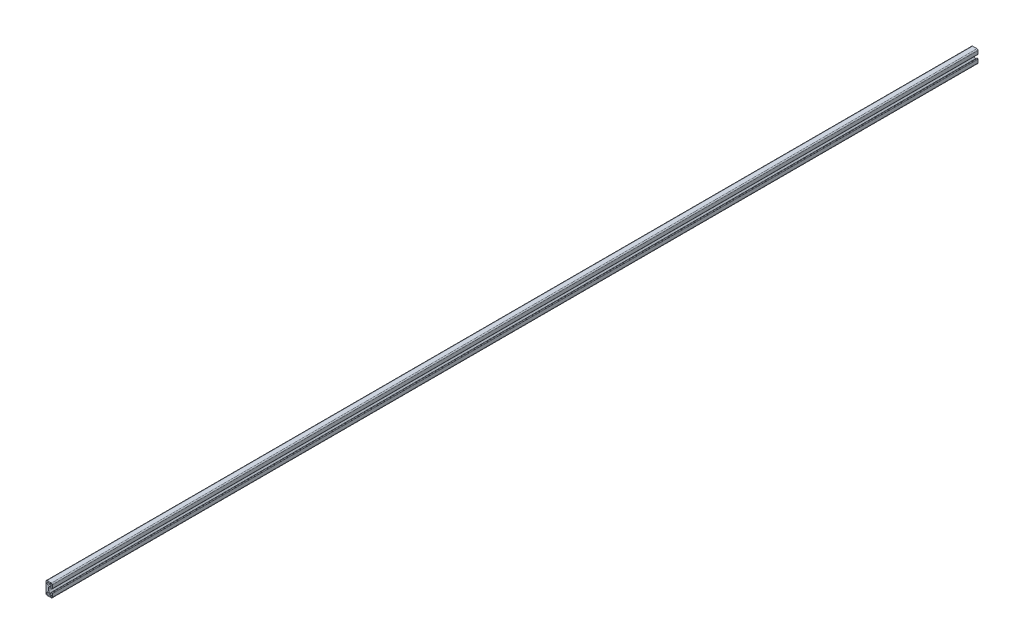
SolidWorks part; units mm, degrees
ref_plane "Front Plane" through (0, 0, 0) normal (0, 0, 1) x (1, 0, 0)
ref_plane "Top Plane" through (0, 0, 0) normal (0, 1, 0) x (1, 0, 0)
ref_plane "Right Plane" through (0, 0, 0) normal (1, 0, 0) x (0, 0, -1)
sketch "Sketch1" plane through (0, 0, 0) normal (0, 0, 1) x (1, 0, 0)
  line L0 (-6.35, 0) -> (6.35, 0) construction
  line L1 (6.35, 4.3011) -> (6.35, 10.5833)
  line L2 (4.2333, 12.7) -> (-4.2333, 12.7)
  line L3 (-6.35, 10.5833) -> (-6.35, 0)
  line L4 (-1.778, 0) -> (-1.778, 1.27)
  line L5 (-0.8467, 3.5339) -> (2.4133, 6.7939)
  line L6 (2.7725, 6.9427) -> (3.048, 6.9427)
  line L7 (3.6407, 6.35) -> (3.6407, 4.3011)
  line L8 (4.6905, 3.2512) -> (5.3001, 3.2512)
  circle A2 centre (3.429, 9.906) radius 1.6933
  circle A3 centre (-2.1167, 8.4667) radius 2.2013
  arc A4 (6.35, 10.5833) -> (4.2333, 12.7) centre (4.2333, 10.5833) ccw
  arc A5 (-4.2333, 12.7) -> (-6.35, 10.5833) centre (-4.2333, 10.5833) ccw
  arc A6 (-0.8467, 3.5339) -> (-1.778, 1.27) centre (1.4393, 1.27) ccw
  arc A7 (2.7725, 6.9427) -> (2.4133, 6.7939) centre (2.7725, 6.4347) ccw
  arc A8 (3.6407, 6.35) -> (3.048, 6.9427) centre (3.048, 6.35) ccw
  arc A9 (3.6407, 4.3011) -> (4.6905, 3.2512) centre (4.6905, 4.3011) ccw
  arc A10 (5.3001, 3.2512) -> (6.35, 4.3011) centre (5.3001, 4.3011) ccw
  dimension "D8" = 2.1167
  dimension "D9" = 3.3867
  dimension "D10" = 4.4027
  dimension "D13" = 1.0499
  dimension "D14" = 3.2173
  dimension "D16" = 0.508
  dimension "D17" = 0.5927
  dimension "Rail Height" = 25.4
  dimension "Rail Width" = 12.7
  dimension "D1" = 4.572
  dimension "D2" = 135
  dimension "D3" = 1.27
  dimension "D4" = 16.9333
  dimension "D5" = 4.2333
  dimension "D7" = 2.921
  dimension "D6" = 19.812
  dimension "TSlot Wdith" = 6.5024
  dimension "D11" = 2.7093
  dimension "D12" = 6.9427
  dimension "D15" = 5.5033
sketch "Sketch2" plane through (0, 0, 0) normal (1, 0, 0) x (0, 0, -1)
  line L0 (-914.4, 0) -> (914.4, 0)
  point P2 (-876.3, 0)
  point P3 (876.3, 0)
  dimension "Length" = 1828.8
  dimension "D1" = 38.1
  dimension "D2" = 38.1
sketch "Sketch3" plane through (0, 0, 0) normal (0, 0, 1) x (1, 0, 0)
  line L0 (-1.778, 0) -> (-1.778, 1.27) construction
  line L1 (-0.8467, 3.5339) -> (2.4133, 6.7939) construction
  line L2 (2.7725, 6.9427) -> (3.048, 6.9427) construction
  line L3 (3.6407, 6.35) -> (3.6407, 4.3011) construction
  line L4 (4.6905, 3.2512) -> (5.3001, 3.2512) construction
  line L5 (6.35, 4.3011) -> (6.35, 10.5833) construction
  line L6 (4.2333, 12.7) -> (-4.2333, 12.7) construction
  line L7 (-6.35, 10.5833) -> (-6.35, 0) construction
  line L8 (-1.778, 0) -> (-1.778, 1.27)
  line L9 (-0.8467, 3.5339) -> (2.4133, 6.7939)
  line L10 (2.7725, 6.9427) -> (3.048, 6.9427)
  line L11 (3.6407, 6.35) -> (3.6407, 4.3011)
  line L12 (4.6905, 3.2512) -> (5.3001, 3.2512)
  line L13 (6.35, 4.3011) -> (6.35, 10.5833)
  line L14 (4.2333, 12.7) -> (-4.2333, 12.7)
  line L15 (-6.35, 10.5833) -> (-6.35, 0)
  line L16 (-6.35, 0) -> (-1.778, 0)
  arc A0 (-0.8467, 3.5339) -> (-1.778, 1.27) centre (1.4393, 1.27) ccw construction
  circle A1 centre (-2.1167, 8.4667) radius 2.2013
  circle A2 centre (-2.1167, 8.4667) radius 2.2013
  circle A3 centre (3.429, 9.906) radius 1.6933
  circle A4 centre (3.429, 9.906) radius 1.6933
  arc A5 (2.7725, 6.9427) -> (2.4133, 6.7939) centre (2.7725, 6.4347) ccw construction
  arc A6 (3.6407, 6.35) -> (3.048, 6.9427) centre (3.048, 6.35) ccw construction
  arc A7 (3.6407, 4.3011) -> (4.6905, 3.2512) centre (4.6905, 4.3011) ccw construction
  arc A8 (5.3001, 3.2512) -> (6.35, 4.3011) centre (5.3001, 4.3011) ccw construction
  arc A9 (6.35, 10.5833) -> (4.2333, 12.7) centre (4.2333, 10.5833) ccw construction
  arc A10 (-4.2333, 12.7) -> (-6.35, 10.5833) centre (-4.2333, 10.5833) ccw construction
  arc A11 (-0.8467, 3.5339) -> (-1.778, 1.27) centre (1.4393, 1.27) ccw
  arc A12 (2.7725, 6.9427) -> (2.4133, 6.7939) centre (2.7725, 6.4347) ccw
  arc A13 (3.6407, 6.35) -> (3.048, 6.9427) centre (3.048, 6.35) ccw
  arc A14 (3.6407, 4.3011) -> (4.6905, 3.2512) centre (4.6905, 4.3011) ccw
  arc A15 (5.3001, 3.2512) -> (6.35, 4.3011) centre (5.3001, 4.3011) ccw
  arc A16 (6.35, 10.5833) -> (4.2333, 12.7) centre (4.2333, 10.5833) ccw
  arc A17 (-4.2333, 12.7) -> (-6.35, 10.5833) centre (-4.2333, 10.5833) ccw
  dimension "D1" = 0
  dimension "D2" = 0
extrude "Boss-Extrude1" add sketch "Sketch3" along normal mid plane 1828.8
mirror "Mirror1" about plane through (0, 0, 0) normal (0, 1, 0) of bodies 104
equation "\"D1@Sketch1\"=\"Rail Width@Sketch1\"*0.36"
equation "\"D3@Sketch1\"=\"Rail Height@Sketch1\"*0.05"
equation "\"D4@Sketch1\"=\"Rail Height@Sketch1\"*2/3"
equation "\"D5@Sketch1\"=\"D4@Sketch1\"*1/4"
equation "\"D7@Sketch1\"=\"Rail Width@Sketch1\"*0.23"
equation "\"D6@Sketch1\"=\"Rail Height@Sketch1\"*0.78"
equation "\"D8@Sketch1\"=\"D4@Sketch1\"*1/8"
equation "\"D9@Sketch1\"=\"D4@Sketch1\"*1/5"
equation "\"D10@Sketch1\"=\"D4@Sketch1\"*0.26"
equation "\"D11@Sketch1\"=\"D4@Sketch1\"*0.16"
equation "\"D12@Sketch1\"=\"D4@Sketch1\"*0.41"
equation "\"D13@Sketch1\"=\"D4@Sketch1\"*0.062"
equation "\"D14@Sketch1\"=\"D9@Sketch1\"*0.95"
equation "\"D15@Sketch1\"=\"D4@Sketch1\"*0.325"
equation "\"D16@Sketch1\"=\"D4@Sketch1\"*0.03"
equation "\"D17@Sketch1\"=\"D4@Sketch1\"*0.035"
equation "\"D2@Sketch2\"=\"D1@Sketch2\""
equation "\"D1@Boss-Extrude1\"=\"length@sketch2\""
